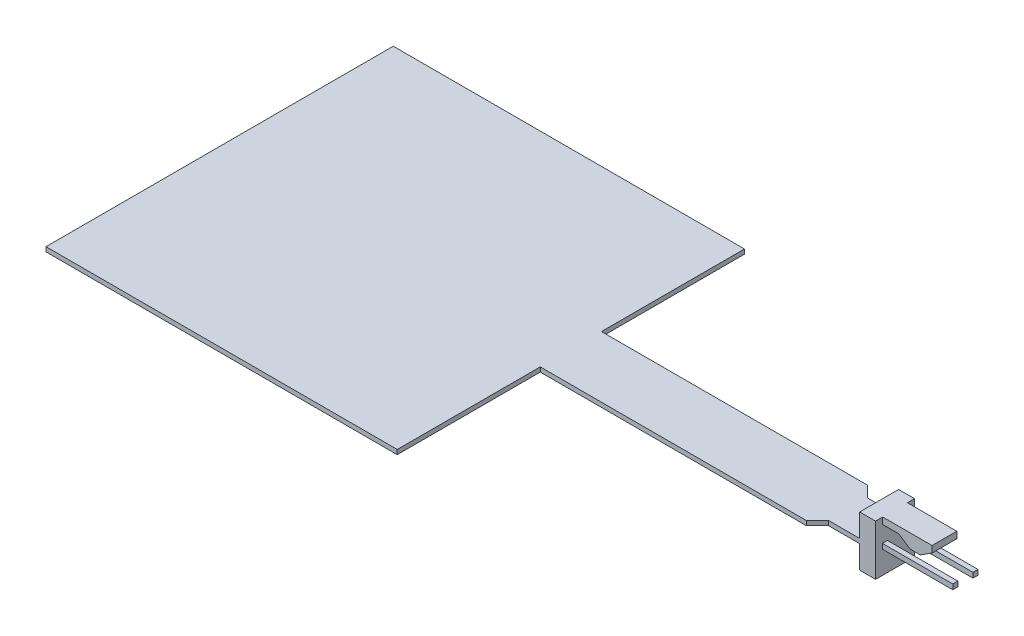
SolidWorks part; units mm, degrees
ref_plane "Front Plane" through (0, 0, 0) normal (0, 0, 1) x (1, 0, 0)
ref_plane "Top Plane" through (0, 0, 0) normal (0, 1, 0) x (1, 0, 0)
ref_plane "Right Plane" through (0, 0, 0) normal (1, 0, 0) x (0, 0, -1)
sketch "Sketch1" plane through (0, 0, 0) normal (0, 1, 0) x (1, 0, 0)
  line L0 (0, 0) -> (55.58, 0) construction
  line L1 (22.1, 3.85) -> (55.58, 3.85)
  line L3 (22.1, -3.85) -> (55.58, -3.85)
  line L4 (55.58, 3.85) -> (55.58, -3.85) construction
  line L5 (22.1, 3.85) -> (22.1, 21.85)
  line L6 (55.58, 3.85) -> (56.98, 2.45)
  line L7 (56.98, 2.45) -> (60.9, 2.45)
  line L8 (60.9, 2.45) -> (60.9, -2.45)
  line L9 (60.9, -2.45) -> (56.98, -2.45)
  line L10 (56.98, -2.45) -> (55.58, -3.85)
  line L11 (55.58, 0) -> (60.9, 0) construction
  line L14 (-22.1, -21.85) -> (22.1, -21.85)
  line L15 (-22.1, -21.85) -> (-22.1, 21.85)
  line L16 (-22.1, 21.85) -> (22.1, 21.85)
  line L17 (22.1, -21.85) -> (22.1, -3.85)
  line L18 (-22.1, -21.85) -> (22.1, 21.85) construction
  line L19 (-22.1, 21.85) -> (22.1, -21.85) construction
  dimension "D1" = 83
  dimension "D3" = 43.7
  dimension "D2" = 7.7
  dimension "D4" = 4.9
  dimension "D5" = 45
  dimension "D6" = 44.2
  dimension "D7" = 5.32
extrude "Boss-Extrude1" add sketch "Sketch1" along normal mid plane 0.57
sketch "Sketch2" plane through (60.9, 0, 0) normal (1, 0, 0) x (0, 0, -1)
  line L0 (-2.45, -3.175) -> (2.45, 3.175) construction
  line L1 (-2.45, -3.175) -> (2.45, -3.175)
  line L2 (-2.45, -3.175) -> (-2.45, 3.175)
  line L3 (-2.45, 3.175) -> (2.45, 3.175)
  line L4 (2.45, -3.175) -> (2.45, 3.175)
  point P4 (0, 0)
  dimension "D1" = 6.35
  dimension "D2" = 4.9
extrude "Boss-Extrude2" add sketch "Sketch2" along normal blind 2
sketch "Sketch3" plane through (0, 0, 0) normal (0, 0, 1) x (1, 0, 0)
  line L0 (62.9, 3.175) -> (69.11, 3.175)
  line L1 (69.11, 3.175) -> (69.11, 2.355)
  line L2 (69.11, 2.355) -> (67.63, 1.405)
  line L3 (67.63, 1.405) -> (66.38, 1.405)
  line L4 (66.38, 1.405) -> (64.9, 2.355)
  line L5 (64.9, 2.355) -> (62.9, 2.355)
  line L6 (62.9, 3.175) -> (62.9, -3.175) construction
  line L7 (62.9, 2.355) -> (62.9, 3.175)
  line L8 (60.9, 3.175) -> (60.9, 0.285) construction
  line L9 (64.9, 2.355) -> (69.11, 2.355) construction
  line L10 (67.005, 1.405) -> (67.005, 2.355) construction
  dimension "D1" = 8.21
  dimension "D2" = 0.82
  dimension "D3" = 1.77
  dimension "D4" = 2
  dimension "D5" = 1.25
extrude "Boss-Extrude3" add sketch "Sketch3" along normal mid plane 3.11
sketch "Sketch4" plane through (62.9, 0, 0) normal (1, 0, 0) x (0, 0, -1)
  line L0 (-2.45, 0) -> (2.45, 0) construction
  line L1 (2.45, 0.285) -> (2.45, -0.285) construction
  line L2 (-0.9525, -0.3175) -> (0.9525, -0.3175) construction
  line L3 (-1.5875, -0.3175) -> (-0.9525, -0.3175)
  line L4 (-1.5875, -0.3175) -> (-1.5875, 0.3175)
  line L5 (-1.5875, 0.3175) -> (-0.9525, 0.3175)
  line L6 (-0.9525, -0.3175) -> (-0.9525, 0.3175)
  line L7 (-1.5875, -0.3175) -> (-0.9525, 0.3175) construction
  line L8 (-1.5875, 0.3175) -> (-0.9525, -0.3175) construction
  line L9 (0.9525, -0.3175) -> (1.5875, -0.3175)
  line L10 (0.9525, -0.3175) -> (0.9525, 0.3175)
  line L11 (0.9525, 0.3175) -> (1.5875, 0.3175)
  line L12 (1.5875, -0.3175) -> (1.5875, 0.3175)
  line L13 (0.9525, -0.3175) -> (1.5875, 0.3175) construction
  line L14 (0.9525, 0.3175) -> (1.5875, -0.3175) construction
  line L15 (0, 0) -> (0, -0.3175) construction
  point P0 (-1.27, 0)
  point P6 (0, 0)
  point P12 (1.27, 0)
  dimension "D1" = 0.635
  dimension "D2" = 2.54
extrude "Boss-Extrude4" add sketch "Sketch4" along normal offset from surface (8.85 mm away) 10.85
